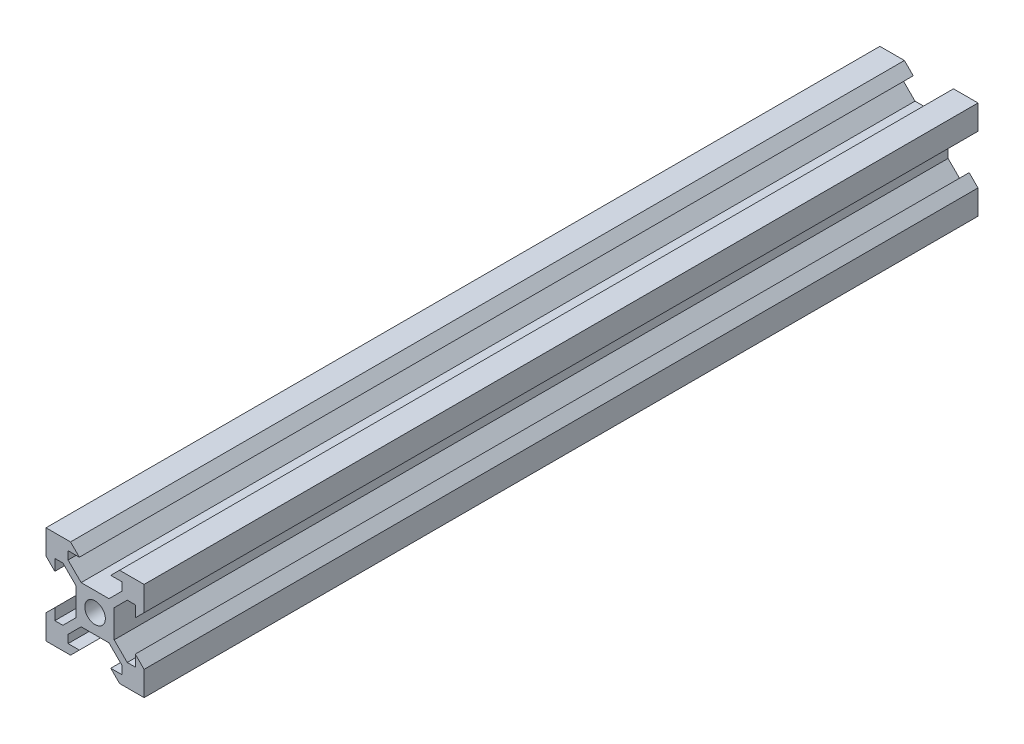
SolidWorks part; units mm, degrees
ref_plane "Front Plane" through (0, 0, 0) normal (0, 0, 1) x (1, 0, 0)
ref_plane "Top Plane" through (0, 0, 0) normal (0, 1, 0) x (1, 0, 0)
ref_plane "Right Plane" through (0, 0, 0) normal (1, 0, 0) x (0, 0, -1)
sketch "Sketch1" plane through (0, 0, 0) normal (0, 0, 1) x (1, 0, 0)
  line L0 (-10, 10) -> (-10, 5)
  line L1 (-10, 5) -> (-8.2, 3.2)
  line L2 (-8.2, 3.2) -> (-8.2, 5.4993)
  line L3 (-8.2, 5.4993) -> (-6.56, 5.4993)
  line L4 (-6.56, 5.4993) -> (-3.9007, 2.84)
  line L5 (-3.9007, 2.84) -> (-3.9007, -2.84)
  line L6 (-3.9007, -2.84) -> (-6.56, -5.4993)
  line L7 (-6.56, -5.4993) -> (-8.2, -5.4993)
  line L8 (-8.2, -5.4993) -> (-8.2, -3.2)
  line L9 (-8.2, -3.2) -> (-10, -5)
  line L10 (-10, -5) -> (-10, -10)
  line L11 (-10, -10) -> (-5, -10)
  line L12 (-5, -10) -> (-3.2, -8.2)
  line L13 (-3.2, -8.2) -> (-5.4993, -8.2)
  line L14 (-5.4993, -8.2) -> (-5.4993, -6.56)
  line L15 (-5.4993, -6.56) -> (-2.84, -3.9007)
  line L16 (-2.84, -3.9007) -> (2.84, -3.9007)
  line L17 (2.84, -3.9007) -> (5.4993, -6.56)
  line L18 (5.4993, -6.56) -> (5.4993, -8.2)
  line L19 (5.4993, -8.2) -> (3.2, -8.2)
  line L20 (3.2, -8.2) -> (5, -10)
  line L21 (5, -10) -> (10, -10)
  line L22 (10, -10) -> (10, -5)
  line L23 (10, -5) -> (8.2, -3.2)
  line L24 (8.2, -3.2) -> (8.2, -5.4993)
  line L25 (8.2, -5.4993) -> (6.56, -5.4993)
  line L26 (6.56, -5.4993) -> (3.9007, -2.84)
  line L27 (3.9007, -2.84) -> (3.9007, 2.84)
  line L28 (3.9007, 2.84) -> (6.56, 5.4993)
  line L29 (6.56, 5.4993) -> (8.2, 5.4993)
  line L30 (8.2, 5.4993) -> (8.2, 3.2)
  line L31 (8.2, 3.2) -> (10, 5)
  line L32 (10, 5) -> (10, 10)
  line L33 (10, 10) -> (5, 10)
  line L34 (5, 10) -> (3.2, 8.2)
  line L35 (3.2, 8.2) -> (5.4993, 8.2)
  line L36 (5.4993, 8.2) -> (5.4993, 6.56)
  line L37 (5.4993, 6.56) -> (2.84, 3.9007)
  line L38 (2.84, 3.9007) -> (-2.84, 3.9007)
  line L39 (-2.84, 3.9007) -> (-5.4993, 6.56)
  line L40 (-5.4993, 6.56) -> (-5.4993, 8.2)
  line L41 (-5.4993, 8.2) -> (-3.2, 8.2)
  line L42 (-3.2, 8.2) -> (-5, 10)
  line L43 (-5, 10) -> (-10, 10)
  circle A0 centre (0, 0) radius 2.1
extrude "Boss-Extrude1" add sketch "Sketch1" against normal blind 170
ref_plane "基准面1" through (0, 0, 0) normal (0, 0, 1) x (1, 0, 0)
